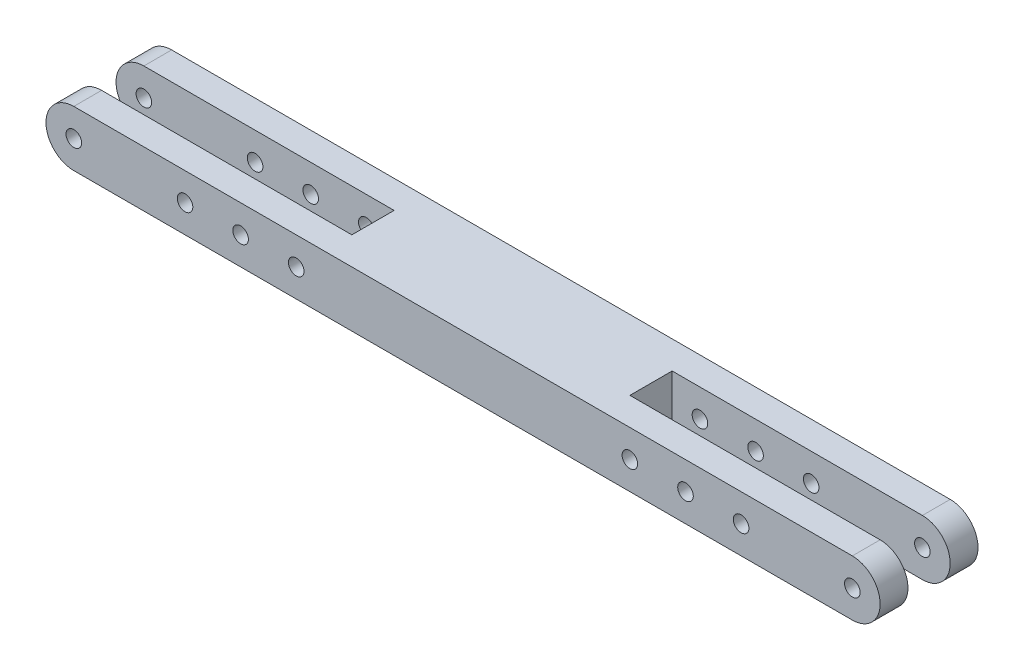
SolidWorks part; units mm, degrees
ref_plane "Front Plane" through (0, 0, 0) normal (0, 0, 1) x (1, 0, 0)
ref_plane "Top Plane" through (0, 0, 0) normal (0, 1, 0) x (1, 0, 0)
ref_plane "Right Plane" through (0, 0, 0) normal (1, 0, 0) x (0, 0, -1)
sketch "Sketch2" plane through (0, 0, 0) normal (0, 0, 1) x (1, 0, 0)
  line L0 (0, 6.35) -> (177.8, 6.35)
  line L1 (0, -6.35) -> (177.8, -6.35)
  line L2 (-6.35, 0) -> (184.15, 0) construction
  line L3 (88.9, 6.35) -> (88.9, -6.35) construction
  arc A0 (0, 6.35) -> (0, -6.35) centre (0, 0) ccw
  circle A1 centre (0, 0) radius 1.778
  circle A2 centre (25.4, 0) radius 1.778
  circle A3 centre (38.1, 0) radius 1.778
  circle A4 centre (50.8, 0) radius 1.778
  circle A5 centre (127, 0) radius 1.778
  circle A6 centre (139.7, 0) radius 1.778
  circle A7 centre (152.4, 0) radius 1.778
  circle A8 centre (177.8, 0) radius 1.778
  arc A9 (177.8, 6.35) -> (177.8, -6.35) centre (177.8, 0) cw
  point P16 (88.9, 0)
  dimension "D1" = 12.7
  dimension "D4" = 3.556
  dimension "D5" = 3.556
  dimension "D6" = 3.556
  dimension "D7" = 3.556
  dimension "D2" = 88.9
  dimension "D8" = 25.4
  dimension "D9" = 12.7
  dimension "D10" = 12.7
extrude "Boss-Extrude1" add sketch "Sketch2" along normal blind 22.352
sketch "Sketch3" plane through (0, 0, 0) normal (0, 1, 0) x (1, 0, 0)
  line L0 (-6.35, -11.176) -> (184.15, -11.176) construction
  line L1 (-6.35, 0) -> (-6.35, -22.352) construction
  line L2 (184.15, -22.352) -> (184.15, 0) construction
  line L3 (177.8, 0) -> (0, 0) construction
  line L4 (-6.35, -6.35) -> (57.15, -6.35)
  line L5 (-6.35, -6.35) -> (-6.35, -16.002)
  line L6 (-6.35, -16.002) -> (57.15, -16.002)
  line L7 (57.15, -6.35) -> (57.15, -16.002)
  line L8 (184.15, -6.35) -> (120.65, -6.35)
  line L9 (184.15, -6.35) -> (184.15, -16.002)
  line L10 (184.15, -16.002) -> (120.65, -16.002)
  line L11 (120.65, -6.35) -> (120.65, -16.002)
  dimension "D1" = 9.652
  dimension "D2" = 9.652
  dimension "D3" = 6.35
  dimension "D4" = 6.35
  dimension "D5" = 63.5
  dimension "D6" = 63.5
extrude "Cut-Extrude1" cut sketch "Sketch3" against normal through all both and the other way through all
